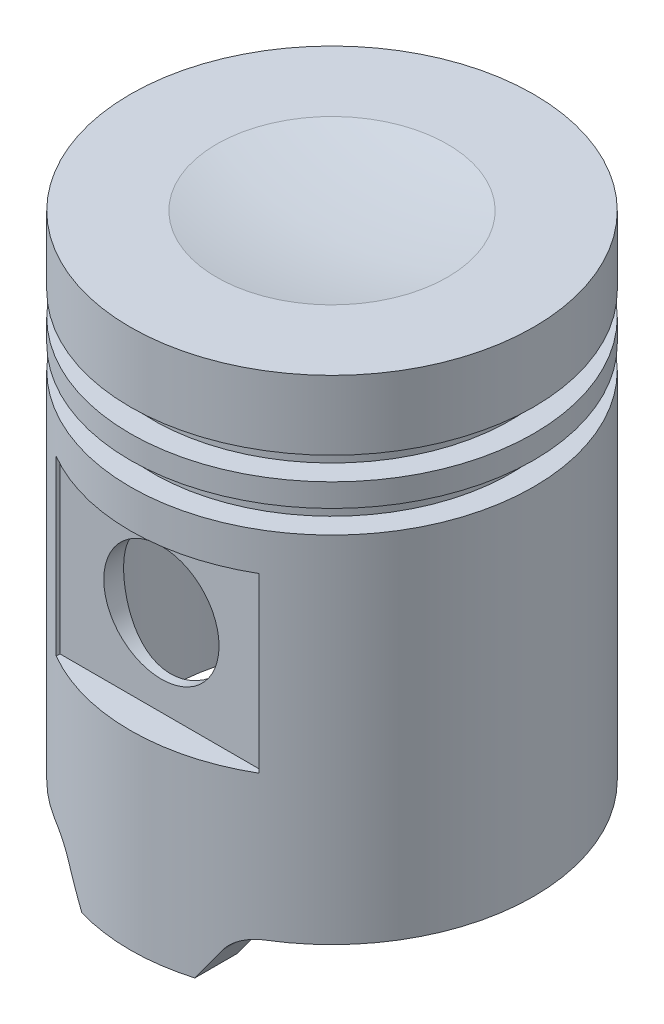
SolidWorks part; units mm, degrees
ref_plane "Front Plane" through (0, 0, 0) normal (0, 0, 1) x (1, 0, 0)
ref_plane "Top Plane" through (0, 0, 0) normal (0, 1, 0) x (1, 0, 0)
ref_plane "Right Plane" through (0, 0, 0) normal (1, 0, 0) x (0, 0, -1)
sketch "Sketch1" plane through (0, 0, 0) normal (0, 0, 1) x (1, 0, 0)
  line L0 (0, 0) -> (22.225, 0)
  line L1 (22.225, 0) -> (22.225, 44.196)
  line L2 (22.225, 44.196) -> (19.685, 44.196)
  line L3 (19.685, 44.196) -> (19.685, 46.736)
  line L4 (19.685, 46.736) -> (22.225, 46.736)
  line L5 (22.225, 46.736) -> (22.225, 49.276)
  line L6 (22.225, 49.276) -> (19.685, 49.276)
  line L7 (19.685, 49.276) -> (19.685, 51.816)
  line L8 (19.685, 51.816) -> (22.225, 51.816)
  line L9 (22.225, 51.816) -> (22.225, 59.436)
  line L10 (22.225, 59.436) -> (12.7127, 59.436)
  line L11 (0, 58.166) -> (0, 0)
  arc A0 (0, 58.166) -> (12.7127, 59.436) centre (0, 122.428) ccw
  point P13 (0, 0)
  point P14 (0, 70.2581)
  dimension "D8" = 128.524
  dimension "D1" = 7.62
  dimension "D2" = 2.54
  dimension "D3" = 2.54
  dimension "D4" = 2.54
  dimension "D5" = 2.54
  dimension "D6" = 58.166
  dimension "D7" = 22.225
revolve "Revolve1" add sketch "Sketch1" angle 360 about L11
sketch "Sketch2" plane through (0, 0, 0) normal (0, -1, 0) x (1, 0, 0)
  circle A0 centre (0, 0) radius 17.78
  dimension "D1" = 35.56
extrude "Cut-Extrude1" cut sketch "Sketch2" against normal blind 51.816
sketch "Sketch3" plane through (0, 0, 0) normal (0, 0, 1) x (1, 0, 0)
  line L0 (0, 0) -> (0, 59.436) construction
  line L1 (22.225, 59.436) -> (-22.225, 59.436) construction
  line L2 (-22.225, 0) -> (22.225, 0) construction
  circle A0 centre (0, 30.48) radius 6.35
  point P9 (0, 0)
  dimension "D1" = 12.7
  dimension "D2" = 30.48
extrude "Cut-Extrude2" cut sketch "Sketch3" against normal through all and the other way through all
sketch "Sketch4" plane through (0, 0, 0) normal (0, 0, 1) x (1, 0, 0)
  line L0 (-6.35, 30.48) -> (6.35, 30.48) construction
  line L1 (-11.176, 40.005) -> (11.176, 40.005)
  line L2 (-11.176, 40.005) -> (-11.176, 20.955)
  line L3 (-11.176, 20.955) -> (11.176, 20.955)
  line L4 (11.176, 40.005) -> (11.176, 20.955)
  line L5 (0, 59.436) -> (0, 0) construction
  line L6 (22.225, 59.436) -> (-22.225, 59.436) construction
  circle A0 centre (0, 30.48) radius 6.35 construction
  dimension "D1" = 22.352
  dimension "D2" = 19.05
  dimension "D3" = 11.176
  dimension "D4" = 9.525
extrude "Cut-Extrude3" cut sketch "Sketch4" against normal through all from offset 18.796 offset against normal yes
mirror "Mirror1" about plane through (0, 0, 0) normal (0, 0, 1) of "Cut-Extrude3"
sketch "Sketch5" plane through (0, 0, 0) normal (0, 0, 1) x (1, 0, 0)
  line L0 (6.223, 0) -> (8.5039, 3.4201)
  line L1 (-22.225, 0) -> (22.225, 0) construction
  line L2 (11.6736, 5.1161) -> (22.225, 5.1161)
  line L3 (22.225, 0) -> (22.225, 44.196) construction
  line L4 (22.225, 5.1161) -> (22.225, 0)
  line L5 (22.225, 0) -> (6.223, 0)
  arc A0 (8.5039, 3.4201) -> (11.6736, 5.1161) centre (11.6736, 1.3061) cw
  dimension "D4" = 3.81
  dimension "D1" = 16.002
  dimension "D2" = 5.1161
  dimension "D3" = 56.3
extrude "Cut-Extrude4" cut sketch "Sketch5" against normal through all and the other way through all
mirror "Mirror2" about plane through (0, 0, 0) normal (1, 0, 0) of "Cut-Extrude4"
